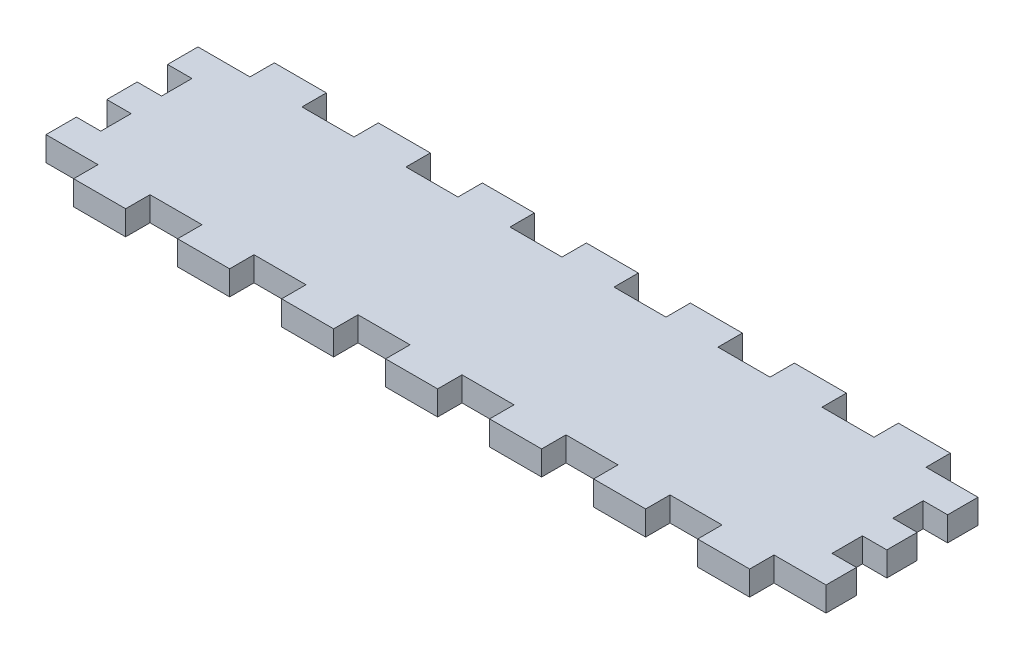
SolidWorks part; units mm, degrees
ref_plane "Front Plane" through (0, 0, 0) normal (0, 0, 1) x (1, 0, 0)
ref_plane "Top Plane" through (0, 0, 0) normal (0, 1, 0) x (1, 0, 0)
ref_plane "Right Plane" through (0, 0, 0) normal (1, 0, 0) x (0, 0, -1)
sketch "Sketch1" plane through (0, 0, 0) normal (0, 1, 0) x (1, 0, 0)
  line L0 (-61.9082, -0.1498) -> (-61.9082, -8.0674)
  line L1 (-61.9082, 15.6854) -> (-48.3615, 15.6854)
  line L2 (-61.9082, 15.6854) -> (-61.9082, 7.7678)
  line L3 (-61.9082, -23.9025) -> (-48.3615, -23.9025)
  line L4 (141.2918, 15.6854) -> (141.2918, 7.7678)
  line L5 (-61.9082, 7.7678) -> (-55.5582, 7.7678)
  line L6 (-61.9082, -15.985) -> (-61.9082, -23.9025)
  line L7 (-61.9082, -0.1498) -> (-55.5582, -0.1498)
  line L8 (-55.5582, 7.7678) -> (-55.5582, -0.1498)
  line L9 (-61.9082, -8.0674) -> (-55.5582, -8.0674)
  line L10 (141.2918, -0.1498) -> (141.2918, -8.0674)
  line L11 (-61.9082, -15.985) -> (-55.5582, -15.985)
  line L12 (-55.5582, -8.0674) -> (-55.5582, -15.985)
  line L13 (141.2918, 7.7678) -> (134.9418, 7.7678)
  line L14 (141.2918, -15.985) -> (141.2918, -23.9025)
  line L15 (141.2918, -0.1498) -> (134.9418, -0.1498)
  line L16 (134.9418, 7.7678) -> (134.9418, -0.1498)
  line L17 (141.2918, -8.0674) -> (134.9418, -8.0674)
  line L18 (-41.5882, 22.0354) -> (-41.5882, -30.2525) construction
  line L19 (141.2918, -15.985) -> (134.9418, -15.985)
  line L20 (134.9418, -8.0674) -> (134.9418, -15.985)
  line L21 (-7.7215, 15.6854) -> (5.8252, 15.6854)
  line L22 (-28.0415, 15.6854) -> (-28.0417, -23.9025) construction
  line L25 (19.3718, 15.6854) -> (32.9185, 15.6854)
  line L26 (-21.2682, 15.6854) -> (-21.2682, 22.0354)
  line L27 (-21.2682, 22.0354) -> (-7.7215, 22.0354)
  line L28 (-7.7215, 15.6854) -> (-7.7215, 22.0354)
  line L29 (46.4652, 15.6854) -> (60.0118, 15.6854)
  line L30 (5.8252, 15.6854) -> (5.8252, 22.0354)
  line L31 (5.8252, 22.0354) -> (19.3718, 22.0354)
  line L32 (19.3718, 15.6854) -> (19.3718, 22.0354)
  line L33 (73.5585, 15.6854) -> (87.1052, 15.6854)
  line L34 (32.9185, 15.6854) -> (32.9185, 22.0354)
  line L35 (32.9185, 22.0354) -> (46.4652, 22.0354)
  line L36 (46.4652, 15.6854) -> (46.4652, 22.0354)
  line L38 (60.0118, 15.6854) -> (60.0118, 22.0354)
  line L39 (60.0118, 22.0354) -> (73.5585, 22.0354)
  line L40 (73.5585, 15.6854) -> (73.5585, 22.0354)
  line L41 (100.6518, 15.6854) -> (114.1985, 15.6854)
  line L42 (87.1052, 15.6854) -> (87.1052, 22.0354)
  line L43 (87.1052, 22.0354) -> (100.6518, 22.0354)
  line L45 (127.7452, 15.6854) -> (141.2918, 15.6854)
  line L48 (100.6518, 15.6854) -> (100.6518, 22.0354)
  line L49 (127.7435, -23.9025) -> (141.2918, -23.9025)
  line L50 (114.1985, 15.6854) -> (114.1985, 22.0354)
  line L51 (114.1985, 22.0354) -> (127.7452, 22.0354)
  line L52 (127.7452, 15.6854) -> (127.7452, 22.0354)
  line L53 (-34.8148, 15.6854) -> (-21.2682, 15.6854)
  line L54 (-48.3615, 15.6854) -> (-48.3615, 22.0354)
  line L55 (-48.3615, 22.0354) -> (-34.8148, 22.0354)
  line L56 (-34.8148, 15.6854) -> (-34.8148, 22.0354)
  line L58 (-48.3615, -23.9025) -> (-48.3615, -30.2525)
  line L59 (-48.3615, -30.2525) -> (-34.8148, -30.2525)
  line L64 (-34.8148, -23.9025) -> (-34.8148, -30.2525)
  line L65 (-34.8148, -23.9025) -> (-21.2687, -23.9025)
  line L66 (-21.2687, -23.9025) -> (-21.2687, -30.2525)
  line L67 (-21.2687, -30.2525) -> (-7.7225, -30.2525)
  line L68 (-7.7225, -23.9025) -> (-7.7225, -30.2525)
  line L69 (-7.7225, -23.9025) -> (5.8237, -23.9025)
  line L70 (5.8237, -23.9025) -> (5.8237, -30.2525)
  line L71 (5.8237, -30.2525) -> (19.3698, -30.2525)
  line L72 (19.3698, -23.9025) -> (19.3698, -30.2525)
  line L73 (19.3698, -23.9025) -> (32.916, -23.9025)
  line L74 (32.916, -23.9025) -> (32.916, -30.2525)
  line L75 (32.916, -30.2525) -> (46.4622, -30.2525)
  line L76 (46.4622, -23.9025) -> (46.4622, -30.2525)
  line L77 (46.4622, -23.9025) -> (60.0083, -23.9025)
  line L78 (60.0083, -23.9025) -> (60.0083, -30.2525)
  line L79 (60.0083, -30.2525) -> (73.5545, -30.2525)
  line L80 (73.5545, -23.9025) -> (73.5545, -30.2525)
  line L81 (73.5545, -23.9025) -> (87.1006, -23.9025)
  line L82 (87.1006, -23.9025) -> (87.1006, -30.2525)
  line L83 (87.1006, -30.2525) -> (100.6468, -30.2525)
  line L88 (100.6468, -23.9025) -> (100.6468, -30.2525)
  line L89 (100.6468, -23.9025) -> (114.1952, -23.9025)
  line L90 (114.1952, -23.9025) -> (114.1952, -30.2525)
  line L91 (114.1952, -30.2525) -> (127.7435, -30.2525)
  line L92 (127.7435, -23.9025) -> (127.7435, -30.2525)
extrude "Boss-Extrude1" add sketch "Sketch1" along normal blind 6.35
